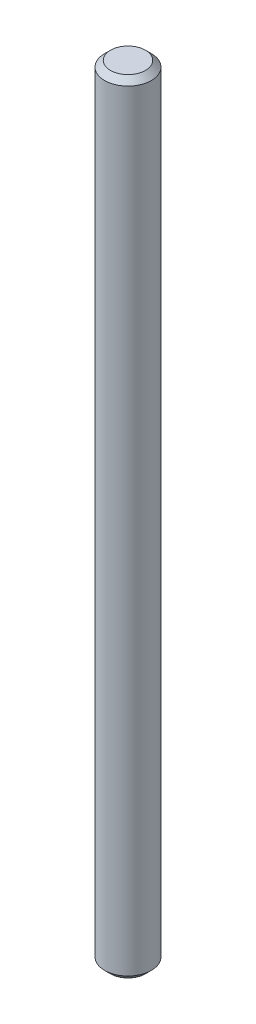
SolidWorks part; units mm, degrees
material "1060 Alloy"
ref_plane "Front Plane" through (0, 0, 0) normal (0, 0, 1) x (1, 0, 0)
ref_plane "Top Plane" through (0, 0, 0) normal (0, 1, 0) x (1, 0, 0)
ref_plane "Right Plane" through (0, 0, 0) normal (1, 0, 0) x (0, 0, -1)
sketch "Sketch1" plane through (0, 0, 0) normal (0, 1, 0) x (1, 0, 0)
  circle A0 centre (0, 0) radius 4
extrude "Boss-Extrude1" add sketch "Sketch1" along normal blind 134
chamfer "Chamfer1" distance 1 angle 45 2 edges at (0, 0, 4) (0, 134, 4)
